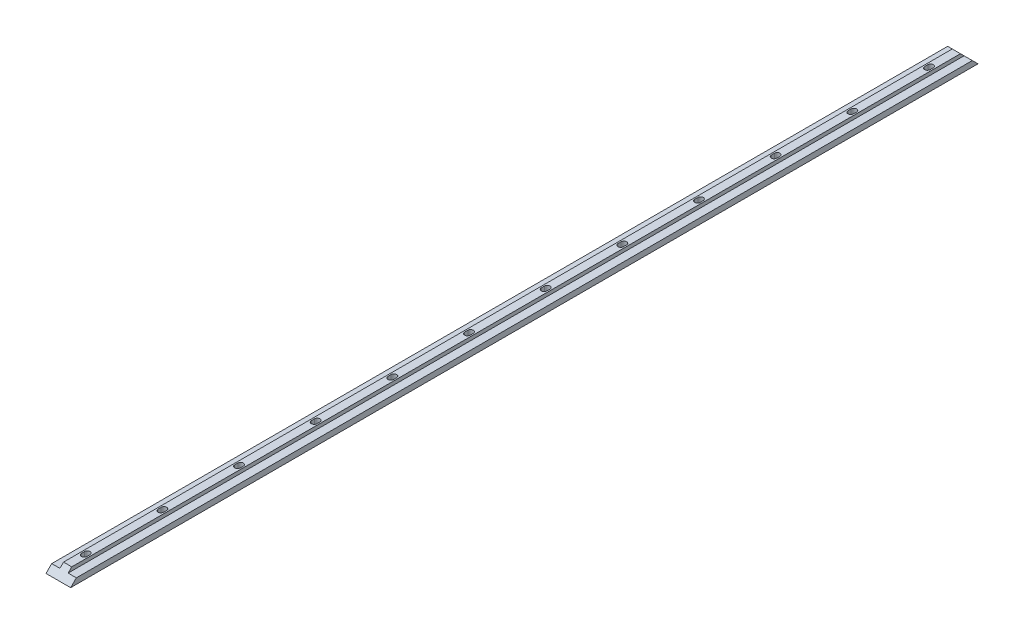
SolidWorks part; units mm, degrees
material "PE1000 Высокой плотности"
ref_plane "Спереди" through (0, 0, 0) normal (0, 0, 1) x (1, 0, 0)
ref_plane "Сверху" through (0, 0, 0) normal (0, 1, 0) x (1, 0, 0)
ref_plane "Справа" through (0, 0, 0) normal (1, 0, 0) x (0, 0, -1)
sketch "Эскиз1" plane through (0, 0, 0) normal (0, 0, 1) x (1, 0, 0)
  line L0 (22.5, 0) -> (-22.5, 0)
  line L1 (-22.5, 0) -> (-22.5, 10.4)
  line L2 (-22.5, 10.4) -> (-7.5, 10.4)
  line L3 (-7.5, 10.4) -> (-7.5, 17)
  line L4 (-7.5, 17) -> (7.5, 17)
  line L5 (0, -9.35) -> (0, 9.35) construction
  line L6 (22.5, 0) -> (22.5, 10.4)
  line L7 (22.5, 10.4) -> (7.5, 10.4)
  line L8 (7.5, 10.4) -> (7.5, 17)
  point P10 (0, 0)
  point P13 (0, 17)
  dimension "D1" = 45
  dimension "D2" = 17
  dimension "D3" = 6.6
  dimension "D4" = 15
extrude "Бобышка-Вытянуть1" add sketch "Эскиз1" along normal mid plane 1657
sketch "Эскиз2" plane through (0, 17, 0) normal (0, 1, 0) x (1, 0, 0)
  line L0 (0, -828.5) -> (0, -778.5) construction
  line L1 (7.5, -828.5) -> (-7.5, -828.5) construction
  circle A0 centre (0, -778.5) radius 3.5
  circle A2 centre (0, -638.5) radius 3.5
  circle A3 centre (0, -498.5) radius 3.5
  circle A4 centre (0, -358.5) radius 3.5
  circle A5 centre (0, -218.5) radius 3.5
  circle A6 centre (0, -78.5) radius 3.5
  circle A7 centre (0, 61.5) radius 3.5
  circle A8 centre (0, 201.5) radius 3.5
  circle A9 centre (0, 341.5) radius 3.5
  circle A10 centre (0, 481.5) radius 3.5
  dimension "D1" = 7
  dimension "D2" = 50
  dimension "D4" = 140
  dimension "D3" = 10
extrude "Вырез-Вытянуть1" cut sketch "Эскиз2" against normal through all
sketch "Эскиз5" plane through (22.5, 0, 0) normal (1, 0, 0) x (0, 0, -1)
  line L0 (-828.5, 0) -> (-811.5, 17)
  line L1 (-828.5, 17) -> (828.5, 17) construction
  line L2 (-811.5, 17) -> (-828.5, 17)
  line L3 (-828.5, 17) -> (-828.5, 0)
  line L4 (0, 9.35) -> (0, -9.35) construction
  line L5 (828.5, 17) -> (828.5, 0)
  line L6 (811.5, 17) -> (828.5, 17)
  line L7 (828.5, 0) -> (811.5, 17)
extrude "Вырез-Вытянуть2" cut sketch "Эскиз5" against normal through all
sketch "Эскиз6" plane through (0, 17, 0) normal (0, 1, 0) x (1, 0, 0)
  line L0 (0, -778.5) -> (0, -772.7265) construction
  line L1 (0, -772.7265) -> (-5, -775.6132) construction
  line L2 (-5, -775.6132) -> (-5, -781.3868)
  line L3 (-5, -781.3868) -> (0, -784.2735) construction
  line L4 (0, -784.2735) -> (5, -781.3868) construction
  line L5 (5, -781.3868) -> (5, -775.6132)
  line L6 (5, -775.6132) -> (0, -772.7265) construction
  circle A0 centre (0, -778.5) radius 5 construction
  arc A6 (-5, -775.6132) -> (5, -775.6132) centre (0, -775.6132) cw
  arc A7 (-5, -781.3868) -> (5, -781.3868) centre (0, -781.3868) ccw
  dimension "D1" = 10
  dimension "D2" = 5
  dimension "D4" = 5
extrude "Вырез-Вытянуть3" cut sketch "Эскиз6" against normal blind 10
pattern_linear "Линейный массив1" count 12 spacing 140 along (0, 0, -1) of "Вырез-Вытянуть3"
move or copy body "Тело-Переместить/Копировать1" [suppressed] bodies to move or copy 105
